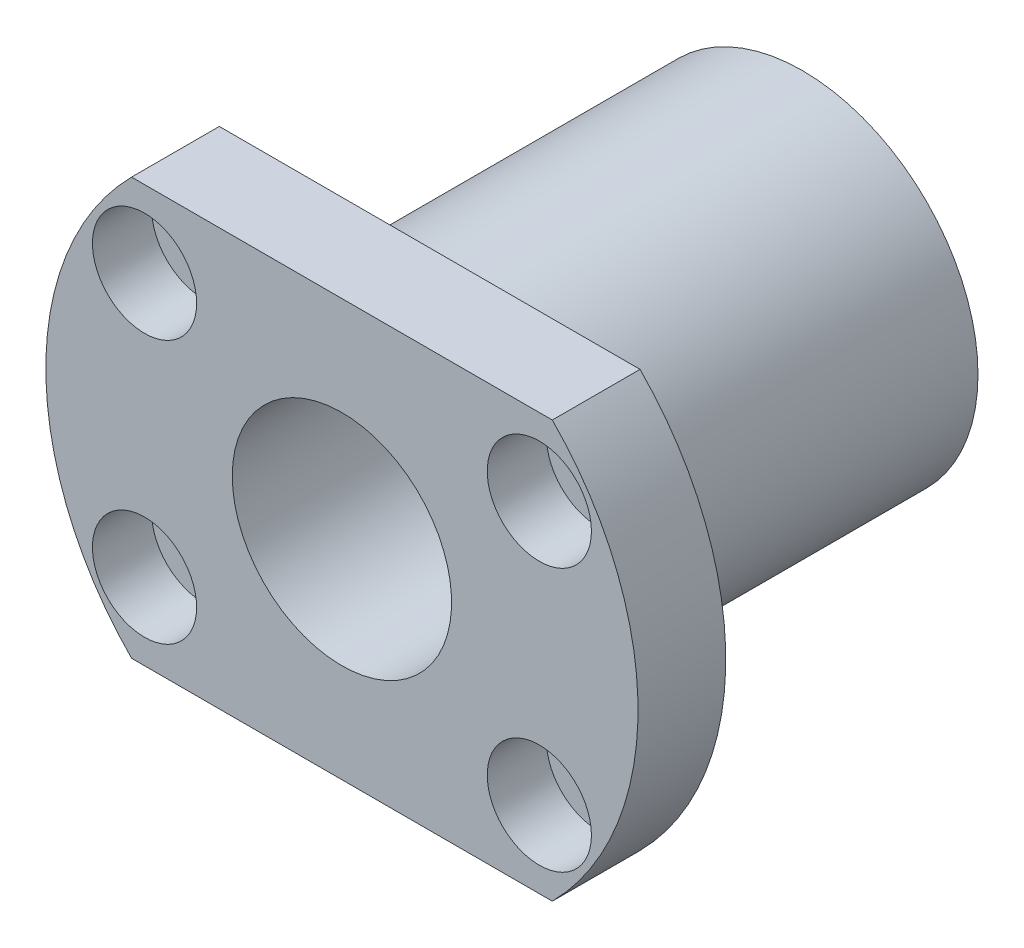
SolidWorks part; units mm, degrees
ref_plane "前视基准面" through (0, 0, 0) normal (0, 0, 1) x (1, 0, 0)
ref_plane "上视基准面" through (0, 0, 0) normal (0, 1, 0) x (1, 0, 0)
ref_plane "右视基准面" through (0, 0, 0) normal (1, 0, 0) x (0, 0, -1)
sketch "草图1" plane through (0, 0, 0) normal (0, -1, 0) x (0, 0, 1)
  line L0 (0, 0) -> (68087.4913, 0) construction
  line L1 (0, 10) -> (42, 10)
  line L2 (42, 10) -> (42, 27)
  line L3 (34, 16) -> (34, 27)
  line L4 (34, 27) -> (42, 27)
  line L11 (34, 16) -> (0, 16)
  line L12 (0, 16) -> (0, 10)
  dimension "D1" = 10
  dimension "D2" = 16
  dimension "D3" = 42
  dimension "D4" = 27
  dimension "D5" = 8
revolve "旋转1" add sketch "草图1" angle 360 about L0
sketch "草图2" plane through (0, 0, 42) normal (0, 0, 1) x (1, 0, 0)
  line L1 (27, -19) -> (-27, -19)
  line L2 (27, -19) -> (27, 19)
  line L3 (27, 19) -> (-27, 19)
  line L4 (-27, -19) -> (-27, 19)
  line L5 (27, -19) -> (-27, 19) construction
  line L6 (27, 19) -> (-27, -19) construction
  circle A0 centre (0, 0) radius 27 construction
  point P0 (0, 0)
  dimension "D1" = 38
extrude "切除-拉伸1" cut sketch "草图2" against normal up to surface (8 mm away) flip side to cut up to face at (-16, 0, 34)
hole_wizard "孔1" positions "草图4" profile "草图3" legacy end condition up to next
sketch "草图4" plane through (0, 0, 42) normal (0, 0, 1) x (1, 0, 0)
  line L1 (-18, -12) -> (18, -12) construction
  line L2 (-18, -12) -> (-18, 12) construction
  line L3 (-18, 12) -> (18, 12) construction
  line L4 (18, -12) -> (18, 12) construction
  line L5 (-18, -12) -> (18, 12) construction
  line L6 (-18, 12) -> (18, -12) construction
  point P0 (-18, -12)
  point P8 (-18, 12)
  point P10 (18, 12)
  point P12 (18, -12)
  point P19 (0, 0)
  dimension "D1" = 36
  dimension "D2" = 24
sketch "草图3" plane through (-18, -12, 42) normal (1, 0, 0) x (0, -1, 0)
  line L0 (0, 0) -> (0, 8)
  line L1 (0, 8) -> (2.75, 8)
  line L2 (2.75, 8) -> (2.75, 5.4)
  line L3 (2.75, 5.4) -> (4.75, 5.4)
  line L4 (4.75, 5.4) -> (4.75, 0)
  line L5 (4.75, 0) -> (0, 0)
  line L6 (0, 110) -> (0, -10) construction
  dimension "直径" = 5.5
  dimension "深度" = 8
  dimension "柱坑直径" = 9.5
  dimension "柱坑深度" = 5.4
